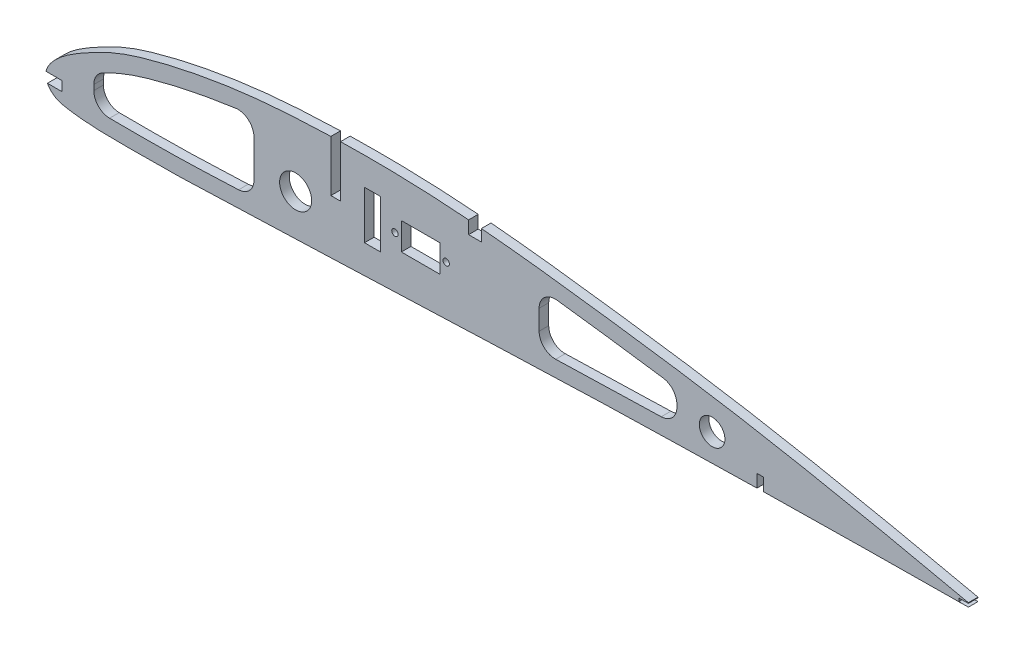
SolidWorks part; units mm, degrees
material "轻木"
ref_plane "前视基准面" through (0, 0, 0) normal (0, 0, 1) x (1, 0, 0)
ref_plane "上视基准面" through (0, 0, 0) normal (0, 1, 0) x (1, 0, 0)
ref_plane "右视基准面" through (0, 0, 0) normal (1, 0, 0) x (0, 0, -1)
other "Configuration Table"
curve "曲线1"
  spline degree 3 poles (300, 0.375, 0) (299.2857, 0.5355, 0) (297.8572, 0.8566, 0) (295.7147, 1.3378, 0) (293.5725, 1.8185, 0) (291.4302, 2.2982, 0) (289.2875, 2.7769, 0) (287.1442, 3.2543, 0) (285.001, 3.7299, 0) (282.8583, 4.2033, 0) (280.7163, 4.6744, 0) (278.5743, 5.1433, 0) (276.432, 5.6099, 0) (274.2889, 6.0741, 0) (272.145, 6.5358, 0) (269.2891, 7.1472, 0) (265.721, 7.9038, 0) (261.4399, 8.8, 0) (257.1573, 9.6847, 0) (252.8725, 10.5577, 0) (248.585, 11.4191, 0) (244.2942, 12.2686, 0) (240.0067, 13.1048, 0) (235.7231, 13.9276, 0) (231.4437, 14.735, 0) (227.1623, 15.5265, 0) (222.8779, 16.3002, 0) (218.5899, 17.0545, 0) (214.2976, 17.7876, 0) (210.0082, 18.4964, 0) (205.7223, 19.1793, 0) (201.441, 19.8388, 0) (197.1575, 20.4787, 0) (192.8717, 21.1016, 0) (188.5834, 21.71, 0) (184.2928, 22.3067, 0) (180.0042, 22.8936, 0) (175.7188, 23.4732, 0) (171.4371, 24.0431, 0) (167.1545, 24.6013, 0) (162.8704, 25.1452, 0) (158.5838, 25.6724, 0) (154.2938, 26.1804, 0) (150.0066, 26.6658, 0) (145.7226, 27.1265, 0) (141.4425, 27.5584, 0) (137.1601, 27.958, 0) (132.875, 28.3213, 0) (128.5869, 28.6439, 0) (124.2953, 28.9218, 0) (120.0053, 29.1506, 0) (115.7177, 29.3264, 0) (111.4337, 29.4514, 0) (107.1488, 29.5275, 0) (102.863, 29.5565, 0) (98.5762, 29.5401, 0) (94.2882, 29.4801, 0) (89.9957, 29.378, 0) (85.6999, 29.236, 0) (81.4026, 29.047, 0) (77.1093, 28.8043, 0) (72.8211, 28.5008, 0) (68.5389, 28.1296, 0) (64.264, 27.6835, 0) (60.7007, 27.2426, 0) (57.8461, 26.8442, 0) (55.696, 26.5216, 0) (53.5496, 26.1773, 0) (51.4067, 25.8115, 0) (49.2673, 25.4247, 0) (47.1314, 25.0171, 0) (44.9882, 24.5868, 0) (42.838, 24.1341, 0) (40.6818, 23.6568, 0) (38.5315, 23.1552, 0) (36.3875, 22.6273, 0) (34.2503, 22.0712, 0) (32.1202, 21.4847, 0) (30.3423, 20.9664, 0) (28.9132, 20.5311, 0) (27.8303, 20.1897, 0) (26.7518, 19.8362, 0) (25.6784, 19.4687, 0) (24.6112, 19.0858, 0) (23.551, 18.6856, 0) (22.4821, 18.2598, 0) (21.4059, 17.8057, 0) (20.3222, 17.3242, 0) (19.2465, 16.8243, 0) (18.1774, 16.3076, 0) (17.1139, 15.7762, 0) (16.0546, 15.2317, 0) (14.9819, 14.6674, 0) (13.8954, 14.0851, 0) (12.7977, 13.4827, 0) (11.7087, 12.8677, 0) (10.6313, 12.2387, 0) (9.5687, 11.5942, 0) (8.5237, 10.9329, 0) (7.6518, 10.3543, 0) (6.9458, 9.8665, 0) (6.3985, 9.4746, 0) (5.8573, 9.0705, 0) (5.3218, 8.651, 0) (4.7913, 8.2128, 0) (4.2653, 7.7527, 0) (3.6165, 7.1497, 0) (2.8604, 6.3846, 0) (2.0362, 5.4343, 0) (1.2959, 4.4252, 0) (0.6772, 3.3675, 0) (0.2189, 2.2697, 0) (-0.0383, 1.1392, 0) (-0.0456, 0.0749, 0) (0.1619, -0.885, 0) (0.4986, -1.7375, 0) (0.9635, -2.5517, 0) (1.5376, -3.3119, 0) (2.2026, -4.0019, 0) (2.94, -4.6051, 0) (3.6355, -5.044, 0) (4.2555, -5.3464, 0) (4.779, -5.5548, 0) (5.3118, -5.728, 0) (5.8521, -5.8723, 0) (6.398, -5.9938, 0) (6.9478, -6.0987, 0) (7.671, -6.2224, 0) (8.5669, -6.3647, 0) (9.636, -6.5177, 0) (10.7063, -6.6545, 0) (11.7778, -6.7754, 0) (12.8506, -6.8809, 0) (13.9246, -6.9713, 0) (14.9978, -7.047, 0) (16.0697, -7.1082, 0) (17.1403, -7.1566, 0) (18.2115, -7.1941, 0) (19.2831, -7.2222, 0) (20.3552, -7.2427, 0) (21.4275, -7.2573, 0) (22.4998, -7.2676, 0) (23.5718, -7.2752, 0) (24.6434, -7.2803, 0) (25.7147, -7.2832, 0) (26.7859, -7.2843, 0) (27.8572, -7.2839, 0) (28.9285, -7.2822, 0) (30.3573, -7.2788, 0) (32.1433, -7.2727, 0) (34.2864, -7.2613, 0) (36.4292, -7.2444, 0) (38.5718, -7.2208, 0) (40.7144, -7.1891, 0) (42.8572, -7.148, 0) (45.0005, -7.0962, 0) (47.1439, -7.0325, 0) (49.2871, -6.9587, 0) (51.4297, -6.8772, 0) (53.572, -6.7902, 0) (55.7143, -6.6999, 0) (57.857, -6.6086, 0) (60.7142, -6.4884, 0) (64.2858, -6.3465, 0) (68.5714, -6.1868, 0) (72.8565, -6.0353, 0) (77.1416, -5.8893, 0) (81.427, -5.7463, 0) (85.7132, -5.6038, 0) (90.0001, -5.4593, 0) (94.287, -5.3101, 0) (98.5731, -5.1566, 0) (102.8583, -4.9992, 0) (107.1431, -4.8383, 0) (111.4281, -4.6742, 0) (115.7138, -4.5074, 0) (120.0001, -4.3383, 0) (124.2865, -4.1673, 0) (128.5722, -3.9953, 0) (132.8572, -3.8233, 0) (137.142, -3.6525, 0) (141.4271, -3.4838, 0) (145.7131, -3.3181, 0) (149.9996, -3.1567, 0) (154.286, -3.0004, 0) (158.5714, -2.8495, 0) (162.8564, -2.7043, 0) (167.1412, -2.5651, 0) (171.4266, -2.4321, 0) (175.7128, -2.3056, 0) (179.9996, -2.1858, 0) (184.2862, -2.0731, 0) (188.5719, -1.9664, 0) (192.857, -1.8646, 0) (197.1419, -1.7668, 0) (201.4272, -1.6719, 0) (205.7132, -1.5788, 0) (209.9999, -1.4865, 0) (214.2864, -1.3941, 0) (218.5722, -1.3027, 0) (222.8572, -1.2136, 0) (227.142, -1.128, 0) (231.4272, -1.0471, 0) (235.7132, -0.9723, 0) (239.9998, -0.9046, 0) (244.2864, -0.8454, 0) (248.5722, -0.7928, 0) (252.8573, -0.7451, 0) (257.1422, -0.7003, 0) (261.4274, -0.6568, 0) (265.7134, -0.6127, 0) (269.2855, -0.574, 0) (272.1433, -0.5408, 0) (274.2862, -0.5157, 0) (276.4287, -0.4908, 0) (278.5712, -0.4671, 0) (280.7137, -0.4452, 0) (282.8567, -0.4258, 0) (285, -0.4096, 0) (287.1432, -0.3973, 0) (289.2862, -0.3884, 0) (291.4287, -0.3824, 0) (293.5711, -0.3786, 0) (295.7137, -0.3765, 0) (297.8567, -0.3754, 0) (299.2855, -0.3751, 0) (300, -0.375, 0) knots 0 0 0 0 0.003574 0.007146 0.010718 0.01429 0.017862 0.021434 0.025008 0.028577 0.032145 0.035713 0.03928 0.042847 0.046415 0.049985 0.057103 0.064219 0.071333 0.078448 0.085563 0.092679 0.099797 0.106885 0.11397 0.121053 0.128137 0.13522 0.142305 0.149391 0.15644 0.163488 0.170534 0.17758 0.184627 0.191675 0.198725 0.205755 0.212782 0.219809 0.226834 0.233861 0.240889 0.24792 0.254921 0.26192 0.268917 0.275914 0.28291 0.289907 0.296905 0.303879 0.310852 0.317824 0.324796 0.331771 0.338748 0.345728 0.352728 0.359727 0.366723 0.373717 0.380709 0.387701 0.394695 0.398233 0.40177 0.405307 0.408843 0.41238 0.415918 0.419457 0.42305 0.426643 0.430235 0.433828 0.43742 0.441014 0.444611 0.446459 0.448306 0.450153 0.451999 0.453844 0.455687 0.45753 0.459459 0.461388 0.463318 0.465249 0.467183 0.469121 0.471062 0.4731 0.475138 0.477173 0.479204 0.481227 0.483239 0.48524 0.486334 0.487428 0.488525 0.48963 0.490748 0.491883 0.493041 0.495071 0.497131 0.499176 0.501171 0.503098 0.50496 0.506796 0.508242 0.509728 0.511253 0.512804 0.514366 0.515919 0.517444 0.518368 0.519283 0.520192 0.521101 0.522011 0.522922 0.523833 0.525592 0.527349 0.529104 0.530859 0.532612 0.534366 0.53612 0.537863 0.539607 0.54135 0.543094 0.544839 0.546584 0.548329 0.550073 0.551817 0.55356 0.555302 0.557045 0.558788 0.560532 0.564019 0.567506 0.570992 0.574478 0.577965 0.581452 0.584939 0.588429 0.591918 0.595406 0.598895 0.602383 0.605872 0.609363 0.616342 0.623319 0.630295 0.637271 0.644247 0.651224 0.658203 0.665183 0.672161 0.679137 0.686114 0.69309 0.700068 0.707048 0.714028 0.721006 0.727983 0.73496 0.741937 0.748915 0.755896 0.762874 0.769851 0.776826 0.783801 0.790777 0.797753 0.804732 0.811709 0.818683 0.825657 0.83263 0.839604 0.846578 0.853555 0.860532 0.867506 0.874479 0.881452 0.888424 0.895399 0.902375 0.90935 0.916324 0.923296 0.930267 0.937239 0.944213 0.951188 0.954676 0.958163 0.961649 0.965135 0.96862 0.972107 0.975595 0.979082 0.982569 0.986054 0.98954 0.993026 0.996512 1 1 1 1
curve "曲线2"
  spline degree 3 poles (299.6892, 0.0825, 0) (300.1498, -0.0478, 0) (299.7114, 0.1074, 0) (299.5104, 0.1872, 0) (299.2477, 0.2871, 0) (298.8504, 0.4413, 0) (298.294, 0.6613, 0) (297.5919, 0.9463, 0) (296.8903, 1.2362, 0) (296.0644, 1.581, 0) (295.1136, 1.9799, 0) (294.0373, 2.431, 0) (292.9597, 2.8788, 0) (291.7683, 3.3665, 0) (290.4608, 3.8877, 0) (289.0365, 4.4399, 0) (287.6073, 4.9796, 0) (286.0635, 5.5484, 0) (284.4048, 6.1444, 0) (282.6311, 6.7664, 0) (280.8534, 7.377, 0) (278.9651, 8.0149, 0) (276.9667, 8.6805, 0) (274.8582, 9.373, 0) (272.7471, 10.0574, 0) (270.5382, 10.7652, 0) (268.2318, 11.4959, 0) (265.8278, 12.2485, 0) (263.4214, 12.9932, 0) (260.9293, 13.7558, 0) (258.3517, 14.5354, 0) (255.6885, 15.3308, 0) (253.0225, 16.1168, 0) (250.2835, 16.9138, 0) (247.4714, 17.7205, 0) (244.5864, 18.536, 0) (241.6982, 19.3402, 0) (238.749, 20.1489, 0) (235.7391, 20.9612, 0) (232.6684, 21.7757, 0) (229.594, 22.5763, 0) (226.4711, 23.374, 0) (223.2997, 24.1675, 0) (220.08, 24.9553, 0) (216.8561, 25.726, 0) (213.5945, 26.4871, 0) (210.2953, 27.2373, 0) (206.9588, 27.975, 0) (203.6178, 28.6919, 0) (200.2497, 29.3918, 0) (196.8549, 30.0732, 0) (193.4336, 30.7349, 0) (190.0077, 31.3718, 0) (186.5618, 31.9862, 0) (183.0963, 32.577, 0) (179.6117, 33.1436, 0) (176.1229, 33.6833, 0) (172.6234, 34.197, 0) (169.1136, 34.6844, 0) (165.5943, 35.1447, 0) (162.0713, 35.5767, 0) (158.5465, 35.9798, 0) (155.0205, 36.3535, 0) (151.4939, 36.6979, 0) (147.9646, 37.0129, 0) (144.4431, 37.2978, 0) (140.9302, 37.5529, 0) (137.4264, 37.7777, 0) (133.9208, 37.9727, 0) (130.4332, 38.1365, 0) (126.9642, 38.269, 0) (123.5147, 38.3706, 0) (120.0643, 38.4412, 0) (116.6408, 38.4803, 0) (113.2449, 38.4881, 0) (109.8772, 38.4649, 0) (106.5099, 38.4098, 0) (103.1795, 38.3231, 0) (99.8867, 38.2053, 0) (96.6323, 38.0567, 0) (93.3796, 37.8749, 0) (90.1728, 37.6618, 0) (87.0127, 37.4182, 0) (83.9, 37.1447, 0) (80.7905, 36.8368, 0) (77.7347, 36.4989, 0) (74.7332, 36.1323, 0) (71.7867, 35.7377, 0) (68.8452, 35.3075, 0) (65.9638, 34.8492, 0) (63.1431, 34.3642, 0) (60.3838, 33.8535, 0) (57.6314, 33.3063, 0) (54.9457, 32.7337, 0) (52.327, 32.1376, 0) (49.7758, 31.5197, 0) (47.2337, 30.8655, 0) (44.763, 30.1905, 0) (42.364, 29.4973, 0) (40.0371, 28.7872, 0) (37.7217, 28.0406, 0) (35.4836, 27.2778, 0) (33.323, 26.5013, 0) (31.2399, 25.7132, 0) (29.1709, 24.8888, 0) (27.1829, 24.0541, 0) (25.2756, 23.212, 0) (23.4491, 22.3647, 0) (21.6401, 21.481, 0) (19.9159, 20.5922, 0) (18.2759, 19.7016, 0) (16.7198, 18.8121, 0) (15.1846, 17.8866, 0) (13.7354, 16.9627, 0) (12.3708, 16.045, 0) (11.0909, 15.1361, 0) (9.8373, 14.192, 0) (8.6721, 13.2572, 0) (7.5935, 12.336, 0) (6.5993, 11.4319, 0) (5.6356, 10.4933, 0) (4.7571, 9.5716, 0) (3.961, 8.6731, 0) (3.2484, 7.802, 0) (2.5791, 6.9017, 0) (2.0018, 6.0303, 0) (1.5119, 5.1928, 0) (1.098, 4.3932, 0) (0.723, 3.565, 0) (0.4148, 2.7772, 0) (0.1635, 2.0409, 0) (-0.0076, 1.362, 0) (-0.0857, 0.6761, 0) (-0.0312, 0.0318, 0) (0.1575, -0.5446, 0) (0.4284, -1.0495, 0) (0.7766, -1.5095, 0) (1.2499, -1.9767, 0) (1.8739, -2.4002, 0) (2.6419, -2.7457, 0) (3.4475, -3.0028, 0) (4.3968, -3.243, 0) (5.4726, -3.4987, 0) (6.6732, -3.7581, 0) (7.8724, -3.9885, 0) (9.2039, -4.2095, 0) (10.6736, -4.4054, 0) (12.2821, -4.571, 0) (13.8972, -4.6995, 0) (15.6445, -4.8094, 0) (17.5211, -4.9053, 0) (19.5261, -4.9826, 0) (21.5305, -5.0368, 0) (23.661, -5.0721, 0) (25.9181, -5.0854, 0) (28.3014, -5.0749, 0) (30.6852, -5.0437, 0) (33.1885, -4.993, 0) (35.8107, -4.9237, 0) (38.5514, -4.8343, 0) (41.2914, -4.7299, 0) (44.1429, -4.6075, 0) (47.1057, -4.467, 0) (50.1792, -4.3077, 0) (53.2522, -4.1367, 0) (56.4269, -3.9498, 0) (59.7026, -3.7473, 0) (63.0791, -3.5293, 0) (66.4551, -3.3033, 0) (69.9209, -3.0645, 0) (73.4761, -2.8134, 0) (77.1202, -2.5502, 0) (80.764, -2.2824, 0) (84.4846, -2.0051, 0) (88.2815, -1.7191, 0) (92.1543, -1.4245, 0) (96.027, -1.128, 0) (99.9621, -0.8252, 0) (103.9592, -0.5167, 0) (108.0179, -0.2032, 0) (112.0767, 0.1098, 0) (116.1823, 0.4251, 0) (120.3344, 0.742, 0) (124.5324, 1.0596, 0) (128.7308, 1.3739, 0) (132.9595, 1.6861, 0) (137.2181, 1.9957, 0) (141.506, 2.3018, 0) (145.7945, 2.6016, 0) (150.096, 2.8954, 0) (154.41, 3.1825, 0) (158.7362, 3.4618, 0) (163.063, 3.7316, 0) (167.3848, 3.9907, 0) (171.7011, 4.2382, 0) (176.0115, 4.4733, 0) (180.3226, 4.6957, 0) (184.6083, 4.9033, 0) (188.8679, 5.0957, 0) (193.1011, 5.2721, 0) (197.335, 5.4325, 0) (201.5222, 5.5742, 0) (205.6623, 5.6969, 0) (209.7546, 5.8004, 0) (213.8473, 5.8854, 0) (217.8716, 5.9498, 0) (221.8268, 5.9942, 0) (225.7124, 6.0188, 0) (229.598, 6.0233, 0) (233.3935, 6.0071, 0) (237.0983, 5.971, 0) (240.7119, 5.9157, 0) (244.325, 5.8393, 0) (247.8275, 5.7436, 0) (251.2186, 5.6301, 0) (254.498, 5.5, 0) (257.7765, 5.3484, 0) (260.9253, 5.1809, 0) (263.9441, 4.9996, 0) (266.8324, 4.8058, 0) (269.7191, 4.5899, 0) (272.4587, 4.362, 0) (275.0509, 4.1249, 0) (277.4951, 3.8799, 0) (279.9368, 3.6105, 0) (282.2113, 3.3338, 0) (284.3185, 3.0537, 0) (286.2585, 2.7745, 0) (288.195, 2.4723, 0) (289.9467, 2.1761, 0) (291.5141, 1.8919, 0) (292.8979, 1.6262, 0) (294.2788, 1.3456, 0) (295.4709, 1.0894, 0) (296.4751, 0.8638, 0) (297.2928, 0.6738, 0) (298.1076, 0.4784, 0) (298.7442, 0.3204, 0) (299.1896, 0.208, 0) (299.4728, 0.1348, 0) (299.6892, 0.0825, 0) (300.1498, -0.0478, 0) (299.7114, 0.1074, 0) knots -0.001345 -0.000897 -0.000449 0 0.000432 0.000863 0.001295 0.001726 0.002951 0.004176 0.0054 0.006625 0.008509 0.010392 0.012274 0.014158 0.016623 0.019088 0.021553 0.024019 0.027053 0.030085 0.033118 0.036152 0.039734 0.043315 0.046896 0.050478 0.054544 0.058608 0.062672 0.066738 0.071224 0.075709 0.080193 0.084679 0.089518 0.094356 0.099193 0.104032 0.10916 0.114286 0.119411 0.124539 0.129889 0.135237 0.140585 0.145936 0.151451 0.156964 0.162478 0.167993 0.173617 0.17924 0.184862 0.190486 0.196184 0.20188 0.207576 0.213274 0.219003 0.22473 0.230457 0.236185 0.241905 0.247622 0.253339 0.259058 0.264725 0.270389 0.276054 0.281721 0.287291 0.29286 0.298428 0.303998 0.309434 0.314867 0.320301 0.325737 0.330995 0.336251 0.341507 0.346766 0.351809 0.356851 0.361892 0.366936 0.371734 0.37653 0.381327 0.386125 0.390654 0.395182 0.399709 0.404238 0.408475 0.41271 0.416945 0.421182 0.425109 0.429034 0.432959 0.436885 0.44048 0.444073 0.447666 0.451261 0.454511 0.457759 0.461007 0.464256 0.467149 0.470041 0.472933 0.475826 0.47836 0.480893 0.483425 0.485956 0.488123 0.490291 0.49246 0.494634 0.496453 0.49827 0.500081 0.501882 0.503328 0.504776 0.506239 0.507727 0.50887 0.510003 0.51111 0.512198 0.513104 0.514027 0.514959 0.515886 0.517235 0.518584 0.51995 0.521324 0.523324 0.525303 0.52727 0.529235 0.531836 0.534446 0.537062 0.539679 0.542921 0.546158 0.549393 0.552628 0.556473 0.560319 0.564166 0.568014 0.57244 0.576864 0.581288 0.585714 0.590681 0.595647 0.600613 0.605581 0.611042 0.616501 0.62196 0.627422 0.633319 0.639214 0.645109 0.651006 0.657275 0.663542 0.669809 0.676078 0.682648 0.689216 0.695784 0.702355 0.70915 0.715943 0.722736 0.729531 0.73647 0.743406 0.750342 0.757281 0.764278 0.771273 0.778268 0.785265 0.792232 0.799197 0.806162 0.81313 0.819969 0.826805 0.833641 0.840479 0.847087 0.853692 0.860297 0.866904 0.873175 0.879445 0.885714 0.891986 0.897819 0.90365 0.909481 0.915314 0.920611 0.925907 0.931202 0.936499 0.941172 0.945842 0.950513 0.955185 0.95915 0.963114 0.967077 0.971042 0.974206 0.977368 0.98053 0.983693 0.985968 0.988241 0.990515 0.992789 0.994144 0.995498 0.996852 0.998206 0.998655 0.999103 0.999551 1 1.000432 1.000863 1.001295 periodic
sketch "草图1" plane through (0, 0, 0) normal (0, 0, 1) x (1, 0, 0)
  line L1 (290, 2.6177) -> (290, -0.3866)
  line L2 (289, 1.8162) -> (289, 0.6101)
  line L3 (0, 0) -> (0, 30) construction
  line L4 (-6, -1.5) -> (6, -1.5)
  line L5 (-6, -1.5) -> (-6, 1.5)
  line L6 (-6, 1.5) -> (6, 1.5)
  line L7 (6, -1.5) -> (6, 1.5)
  line L8 (-6, -1.5) -> (6, 1.5) construction
  line L9 (-6, 1.5) -> (6, -1.5) construction
  line L10 (-1000, 0) -> (49000, 0) construction
  line L11 (90, 29.3715) -> (93, 29.3715)
  line L12 (90, 29.3715) -> (90, 12.3715)
  line L13 (90, 12.3715) -> (93, 12.3715)
  line L14 (93, 29.3715) -> (93, 12.3715)
  line L16 (223, -1.2113) -> (225, -1.2113)
  line L17 (223, -1.2113) -> (223, 3.7887)
  line L18 (223, 3.7887) -> (225, 3.7887)
  line L19 (225, -1.2113) -> (225, 3.7887)
  line L20 (289, 0.6101) -> (286, 0.6101)
  line L21 (289, 0.6101) -> (289, 1.6101)
  line L22 (289, 1.6101) -> (286, 1.6101)
  line L23 (286, 0.6101) -> (286, 1.6101)
  circle A0 centre (79, 8) radius 5
  circle A1 centre (209, 8) radius 4
  spline S0 degree 3 poles (2082.6855, 3477.6386) (932.8124, -150.5674) (615.5616, -70.5075) (295.7147, 1.3378) (293.5725, 1.8185) (291.4302, 2.2982) (289.2875, 2.7769) (287.1442, 3.2543) (285.001, 3.7299) (282.8583, 4.2033) (280.7163, 4.6744) (278.5743, 5.1433) (276.432, 5.6099) (274.2889, 6.0741) (272.145, 6.5358) (269.2891, 7.1472) (265.721, 7.9038) (261.4399, 8.8) (257.1573, 9.6847) (252.8725, 10.5577) (248.585, 11.4191) (244.2942, 12.2686) (240.0067, 13.1048) (234.2978, 14.2013) (228.5907, 15.2685) (222.8779, 16.3002) (218.5899, 17.0545) (214.2976, 17.7876) (210.0082, 18.4964) (205.7223, 19.1793) (201.441, 19.8388) (197.1575, 20.4787) (192.8717, 21.1016) (188.5834, 21.71) (184.2928, 22.3067) (180.0042, 22.8936) (175.7188, 23.4732) (171.4371, 24.0431) (167.1545, 24.6013) (162.8704, 25.1452) (158.5838, 25.6724) (154.2938, 26.1804) (150.0066, 26.6658) (145.7226, 27.1265) (141.4425, 27.5584) (137.1601, 27.958) (132.875, 28.3213) (128.5869, 28.6439) (124.2953, 28.9218) (120.0053, 29.1506) (115.7177, 29.3264) (111.4337, 29.4514) (107.1488, 29.5275) (102.863, 29.5565) (98.5762, 29.5401) (94.2882, 29.4801) (89.9957, 29.378) (85.6999, 29.236) (81.4026, 29.047) (77.1093, 28.8043) (72.8211, 28.5008) (68.5389, 28.1296) (64.264, 27.6835) (60.7007, 27.2426) (57.1284, 26.744) (53.5478, 26.188) (49.9791, 25.5605) (47.1314, 25.0171) (44.9882, 24.5868) (42.838, 24.1341) (40.6818, 23.6568) (38.5315, 23.1552) (36.3875, 22.6273) (34.2503, 22.0712) (32.1202, 21.4847) (30.3423, 20.9664) (28.9132, 20.5311) (27.8303, 20.1897) (26.7518, 19.8362) (25.6784, 19.4687) (24.6112, 19.0858) (23.551, 18.6856) (22.4821, 18.2598) (21.4059, 17.8057) (20.3222, 17.3242) (19.2465, 16.8243) (18.1774, 16.3076) (17.1139, 15.7762) (16.0546, 15.2317) (14.9819, 14.6674) (13.8954, 14.0851) (12.7977, 13.4827) (11.7087, 12.8677) (10.6313, 12.2387) (9.5687, 11.5942) (8.5237, 10.9329) (7.6518, 10.3543) (6.9458, 9.8665) (6.3985, 9.4746) (5.8573, 9.0705) (5.3218, 8.651) (4.7913, 8.2128) (4.2653, 7.7527) (3.6165, 7.1497) (2.8604, 6.3846) (2.0362, 5.4343) (1.2959, 4.4252) (0.6772, 3.3675) (0.2189, 2.2697) (-0.0383, 1.1392) (-0.0456, 0.0749) (0.1619, -0.885) (0.4986, -1.7375) (0.9635, -2.5517) (1.5376, -3.3119) (2.2026, -4.0019) (2.94, -4.6051) (3.6355, -5.044) (4.2555, -5.3464) (4.779, -5.5548) (5.3118, -5.728) (5.8521, -5.8723) (6.398, -5.9938) (6.9478, -6.0987) (7.671, -6.2224) (8.5669, -6.3647) (9.9918, -6.5686) (11.4199, -6.7402) (12.8506, -6.8809) (13.9246, -6.9713) (14.9978, -7.047) (16.0697, -7.1082) (17.1403, -7.1566) (18.2115, -7.1941) (19.2831, -7.2222) (20.3552, -7.2427) (21.4275, -7.2573) (22.4998, -7.2676) (23.5718, -7.2752) (24.6434, -7.2803) (25.7147, -7.2832) (27.143, -7.2847) (28.5715, -7.283) (30.3573, -7.2788) (32.1433, -7.2727) (34.2864, -7.2613) (36.4292, -7.2444) (38.5718, -7.2208) (40.7144, -7.1891) (42.8572, -7.148) (45.0005, -7.0962) (47.1439, -7.0325) (49.2871, -6.9587) (51.4297, -6.8772) (54.2862, -6.7612) (57.1429, -6.6386) (60.7142, -6.4884) (64.2858, -6.3465) (69.9995, -6.1336) (75.7132, -5.9369) (81.427, -5.7463) (85.7132, -5.6038) (90.0001, -5.4593) (94.287, -5.3101) (98.5731, -5.1566) (102.8583, -4.9992) (108.5717, -4.7846) (114.2856, -4.5638) (120.0001, -4.3383) (124.2865, -4.1673) (128.5722, -3.9953) (132.8572, -3.8233) (137.142, -3.6525) (141.4271, -3.4838) (145.7131, -3.3181) (149.9996, -3.1567) (154.286, -3.0004) (158.5714, -2.8495) (164.2846, -2.656) (171.4272, -2.4288) (179.9991, -2.1823) (187.1429, -2.0003) (192.857, -1.8646) (197.1419, -1.7668) (201.4272, -1.6719) (205.7132, -1.5788) (209.9999, -1.4865) (214.2864, -1.3941) (218.5722, -1.3027) (222.8572, -1.2136) (227.142, -1.128) (231.4272, -1.0471) (235.7132, -0.9723) (239.9998, -0.9046) (244.2864, -0.8454) (248.5722, -0.7928) (252.8573, -0.7451) (258.5708, -0.6854) (264.285, -0.6282) (269.2855, -0.574) (272.1433, -0.5408) (274.2862, -0.5157) (276.4287, -0.4908) (278.5712, -0.4671) (280.7137, -0.4452) (282.8567, -0.4258) (285, -0.4096) (287.1432, -0.3973) (289.2862, -0.3884) (291.4287, -0.3824) (293.5711, -0.3786) (295.7137, -0.3765) (545.0303, -0.2592) (793.6356, -11.4767) (1040.5265, 3875.8151) knots -1.589363 -1.589363 -1.589363 -1.589363 0.003574 0.007146 0.010718 0.01429 0.017862 0.021434 0.025008 0.028577 0.032145 0.035713 0.03928 0.042847 0.046415 0.049985 0.057103 0.064219 0.071333 0.078448 0.085563 0.092679 0.099797 0.106885 0.121053 0.128137 0.13522 0.142305 0.149391 0.15644 0.163488 0.170534 0.17758 0.184627 0.191675 0.198725 0.205755 0.212782 0.219809 0.226834 0.233861 0.240889 0.24792 0.254921 0.26192 0.268917 0.275914 0.28291 0.289907 0.296905 0.303879 0.310852 0.317824 0.324796 0.331771 0.338748 0.345728 0.352728 0.359727 0.366723 0.373717 0.380709 0.387701 0.394695 0.398233 0.405307 0.41238 0.415918 0.419457 0.42305 0.426643 0.430235 0.433828 0.43742 0.441014 0.444611 0.446459 0.448306 0.450153 0.451999 0.453844 0.455687 0.45753 0.459459 0.461388 0.463318 0.465249 0.467183 0.469121 0.471062 0.4731 0.475138 0.477173 0.479204 0.481227 0.483239 0.48524 0.486334 0.487428 0.488525 0.48963 0.490748 0.491883 0.493041 0.495071 0.497131 0.499176 0.501171 0.503098 0.50496 0.506796 0.508242 0.509728 0.511253 0.512804 0.514366 0.515919 0.517444 0.518368 0.519283 0.520192 0.521101 0.522011 0.522922 0.523833 0.525592 0.527349 0.530859 0.532612 0.534366 0.53612 0.537863 0.539607 0.54135 0.543094 0.544839 0.546584 0.548329 0.550073 0.551817 0.55356 0.555302 0.558788 0.560532 0.564019 0.567506 0.570992 0.574478 0.577965 0.581452 0.584939 0.588429 0.591918 0.595406 0.598895 0.605872 0.609363 0.616342 0.623319 0.637271 0.644247 0.651224 0.658203 0.665183 0.672161 0.679137 0.686114 0.700068 0.707048 0.714028 0.721006 0.727983 0.73496 0.741937 0.748915 0.755896 0.762874 0.769851 0.776826 0.790777 0.804732 0.818683 0.825657 0.83263 0.839604 0.846578 0.853555 0.860532 0.867506 0.874479 0.881452 0.888424 0.895399 0.902375 0.90935 0.916324 0.923296 0.930267 0.944213 0.951188 0.954676 0.958163 0.961649 0.965135 0.96862 0.972107 0.975595 0.979082 0.982569 0.986054 0.98954 0.993026 0.996512 2.206461 2.206461 2.206461 2.206461 only from (300, 0.375) to (300, -0.375) construction
  spline S1 degree 3 poles (290, 2.6177) (289.0482, 2.8302) (287.3817, 3.2016) (285.001, 3.7299) (282.8583, 4.2033) (280.7163, 4.6744) (278.5743, 5.1433) (276.432, 5.6099) (274.2889, 6.0741) (272.145, 6.5358) (269.2891, 7.1472) (265.721, 7.9038) (261.4399, 8.8) (257.1573, 9.6847) (252.8725, 10.5577) (248.585, 11.4191) (244.2942, 12.2686) (240.0067, 13.1048) (234.2978, 14.2013) (228.5907, 15.2685) (222.8779, 16.3002) (218.5899, 17.0545) (214.2976, 17.7876) (210.0082, 18.4964) (205.7223, 19.1793) (201.441, 19.8388) (197.1575, 20.4787) (192.8717, 21.1016) (188.5834, 21.71) (184.2928, 22.3067) (180.0042, 22.8936) (175.7188, 23.4732) (171.4371, 24.0431) (167.1545, 24.6013) (162.8704, 25.1452) (158.5838, 25.6724) (154.2938, 26.1804) (150.0066, 26.6658) (145.7226, 27.1265) (141.4425, 27.5584) (137.1601, 27.958) (132.875, 28.3213) (128.5869, 28.6439) (124.2953, 28.9218) (120.0053, 29.1506) (115.7177, 29.3264) (111.4337, 29.4514) (107.1488, 29.5275) (102.863, 29.5565) (98.5762, 29.5401) (94.2882, 29.4801) (89.9957, 29.378) (85.6999, 29.236) (81.4026, 29.047) (77.1093, 28.8043) (72.8211, 28.5008) (68.5389, 28.1296) (64.264, 27.6835) (60.7007, 27.2426) (57.1284, 26.744) (53.5478, 26.188) (49.9791, 25.5605) (47.1314, 25.0171) (44.9882, 24.5868) (42.838, 24.1341) (40.6818, 23.6568) (38.5315, 23.1552) (36.3875, 22.6273) (34.2503, 22.0712) (32.1202, 21.4847) (30.3423, 20.9664) (28.9132, 20.5311) (27.8303, 20.1897) (26.7518, 19.8362) (25.6784, 19.4687) (24.6112, 19.0858) (23.551, 18.6856) (22.4821, 18.2598) (21.4059, 17.8057) (20.3222, 17.3242) (19.2465, 16.8243) (18.1774, 16.3076) (17.1139, 15.7762) (16.0546, 15.2317) (14.9819, 14.6674) (13.8954, 14.0851) (12.7977, 13.4827) (11.7087, 12.8677) (10.6313, 12.2387) (9.5687, 11.5942) (8.5237, 10.9329) (7.6518, 10.3543) (6.9458, 9.8665) (6.3985, 9.4746) (5.8573, 9.0705) (5.3218, 8.651) (4.7913, 8.2128) (4.2653, 7.7527) (3.6165, 7.1497) (2.8604, 6.3846) (2.0362, 5.4343) (1.2959, 4.4252) (0.6772, 3.3675) (0.2189, 2.2697) (-0.0383, 1.1392) (-0.0456, 0.0749) (0.1619, -0.885) (0.4986, -1.7375) (0.9635, -2.5517) (1.5376, -3.3119) (2.2026, -4.0019) (2.94, -4.6051) (3.6355, -5.044) (4.2555, -5.3464) (4.779, -5.5548) (5.3118, -5.728) (5.8521, -5.8723) (6.398, -5.9938) (6.9478, -6.0987) (7.671, -6.2224) (8.5669, -6.3647) (9.9918, -6.5686) (11.4199, -6.7402) (12.8506, -6.8809) (13.9246, -6.9713) (14.9978, -7.047) (16.0697, -7.1082) (17.1403, -7.1566) (18.2115, -7.1941) (19.2831, -7.2222) (20.3552, -7.2427) (21.4275, -7.2573) (22.4998, -7.2676) (23.5718, -7.2752) (24.6434, -7.2803) (25.7147, -7.2832) (27.143, -7.2847) (28.5715, -7.283) (30.3573, -7.2788) (32.1433, -7.2727) (34.2864, -7.2613) (36.4292, -7.2444) (38.5718, -7.2208) (40.7144, -7.1891) (42.8572, -7.148) (45.0005, -7.0962) (47.1439, -7.0325) (49.2871, -6.9587) (51.4297, -6.8772) (54.2862, -6.7612) (57.1429, -6.6386) (60.7142, -6.4884) (64.2858, -6.3465) (69.9995, -6.1336) (75.7132, -5.9369) (81.427, -5.7463) (85.7132, -5.6038) (90.0001, -5.4593) (94.287, -5.3101) (98.5731, -5.1566) (102.8583, -4.9992) (108.5717, -4.7846) (114.2856, -4.5638) (120.0001, -4.3383) (124.2865, -4.1673) (128.5722, -3.9953) (132.8572, -3.8233) (137.142, -3.6525) (141.4271, -3.4838) (145.7131, -3.3181) (149.9996, -3.1567) (154.286, -3.0004) (158.5714, -2.8495) (164.2846, -2.656) (171.4272, -2.4288) (179.9991, -2.1823) (187.1429, -2.0003) (192.857, -1.8646) (197.1419, -1.7668) (201.4272, -1.6719) (205.7132, -1.5788) (209.9999, -1.4865) (214.2864, -1.3941) (218.5722, -1.3027) (222.8572, -1.2136) (227.142, -1.128) (231.4272, -1.0471) (235.7132, -0.9723) (239.9998, -0.9046) (244.2864, -0.8454) (248.5722, -0.7928) (252.8573, -0.7451) (258.5708, -0.6854) (264.285, -0.6282) (269.2855, -0.574) (272.1433, -0.5408) (274.2862, -0.5157) (276.4287, -0.4908) (278.5712, -0.4671) (280.7137, -0.4452) (282.8567, -0.4258) (285, -0.4096) (287.1432, -0.3973) (288.8099, -0.3904) (289.7621, -0.3873) (290, -0.3866) knots 0.016674 0.016674 0.016674 0.016674 0.021434 0.025008 0.028577 0.032145 0.035713 0.03928 0.042847 0.046415 0.049985 0.057103 0.064219 0.071333 0.078448 0.085563 0.092679 0.099797 0.106885 0.121053 0.128137 0.13522 0.142305 0.149391 0.15644 0.163488 0.170534 0.17758 0.184627 0.191675 0.198725 0.205755 0.212782 0.219809 0.226834 0.233861 0.240889 0.24792 0.254921 0.26192 0.268917 0.275914 0.28291 0.289907 0.296905 0.303879 0.310852 0.317824 0.324796 0.331771 0.338748 0.345728 0.352728 0.359727 0.366723 0.373717 0.380709 0.387701 0.394695 0.398233 0.405307 0.41238 0.415918 0.419457 0.42305 0.426643 0.430235 0.433828 0.43742 0.441014 0.444611 0.446459 0.448306 0.450153 0.451999 0.453844 0.455687 0.45753 0.459459 0.461388 0.463318 0.465249 0.467183 0.469121 0.471062 0.4731 0.475138 0.477173 0.479204 0.481227 0.483239 0.48524 0.486334 0.487428 0.488525 0.48963 0.490748 0.491883 0.493041 0.495071 0.497131 0.499176 0.501171 0.503098 0.50496 0.506796 0.508242 0.509728 0.511253 0.512804 0.514366 0.515919 0.517444 0.518368 0.519283 0.520192 0.521101 0.522011 0.522922 0.523833 0.525592 0.527349 0.530859 0.532612 0.534366 0.53612 0.537863 0.539607 0.54135 0.543094 0.544839 0.546584 0.548329 0.550073 0.551817 0.55356 0.555302 0.558788 0.560532 0.564019 0.567506 0.570992 0.574478 0.577965 0.581452 0.584939 0.588429 0.591918 0.595406 0.598895 0.605872 0.609363 0.616342 0.623319 0.637271 0.644247 0.651224 0.658203 0.665183 0.672161 0.679137 0.686114 0.700068 0.707048 0.714028 0.721006 0.727983 0.73496 0.741937 0.748915 0.755896 0.762874 0.769851 0.776826 0.790777 0.804732 0.818683 0.825657 0.83263 0.839604 0.846578 0.853555 0.860532 0.867506 0.874479 0.881452 0.888424 0.895399 0.902375 0.90935 0.916324 0.923296 0.930267 0.944213 0.951188 0.954676 0.958163 0.961649 0.965135 0.96862 0.972107 0.975595 0.979082 0.982569 0.98373 0.98373 0.98373 0.98373
  spline S2 degree 1 poles (289, 1.8162) (289, 0.6101) knots 0 0 1 1 construction
  spline S3 degree 3 poles (289, 1.8162) (276.9573, 4.5023) (258.8616, 8.3976) (234.6482, 13.1528) (216.4485, 16.4789) (198.1829, 19.3716) (179.8506, 21.9241) (161.5032, 24.3586) (143.1279, 26.4732) (124.7122, 28.0438) (106.2546, 28.676) (87.7718, 28.43) (72.4033, 27.5865) (60.1859, 26.2263) (51.081, 24.7981) (42.0339, 23.0001) (34.582, 21.1749) (28.6974, 19.4456) (24.362, 17.9834) (20.1748, 16.2079) (16.0789, 14.1399) (12.0403, 11.9468) (8.1401, 9.5604) (5.1537, 7.3164) (3.1001, 5.2006) (1.8138, 3.4707) (0.9689, 1.5796) (0.9059, -0.2656) (1.7459, -2.0716) (3.1431, -3.6011) (4.8543, -4.6194) (6.9276, -5.1056) (9.209, -5.4548) (12.22, -5.8429) (16.0201, -6.1427) (20.6095, -6.2611) (25.2315, -6.2869) (31.3974, -6.2803) (39.1073, -6.2407) (48.3368, -6.0221) (57.5799, -5.613) (66.8407, -5.2429) (76.0966, -4.9217) (88.436, -4.516) (103.8531, -3.9731) (122.3546, -3.2481) (140.8578, -2.4955) (159.3685, -1.8041) (177.8842, -1.2225) (196.4034, -0.7749) (214.9166, -0.3802) (233.434, 0.0126) (251.9612, 0.2567) (270.4719, 0.4292) (282.8248, 0.5874) (289, 0.6101) knots 0.017978 0.017978 0.017978 0.017978 0.078237 0.108366 0.138495 0.168624 0.198753 0.228882 0.259011 0.28914 0.319269 0.349398 0.379527 0.394592 0.409656 0.424721 0.439785 0.447318 0.45485 0.462382 0.469915 0.477447 0.484979 0.492511 0.496277 0.500044 0.50381 0.507576 0.511342 0.515108 0.518874 0.52264 0.526407 0.530173 0.537705 0.545237 0.552769 0.560302 0.575366 0.590431 0.605495 0.62056 0.635624 0.650689 0.680818 0.710947 0.741076 0.771205 0.801334 0.831463 0.861593 0.891722 0.921851 0.95198 0.982109 0.982109 0.982109 0.982109
  point P8 (0, 0)
  dimension "D9" = 10
  dimension "D10" = 8
  dimension "D1" = 290
  dimension "D2" = 1
  dimension "D3" = 12
  dimension "D4" = 3
  dimension "D5" = 30
  dimension "D6" = 3
  dimension "D7" = 17
  dimension "D8" = 90
  dimension "D11" = 130
  dimension "D12" = 11
  dimension "D13" = 8
  dimension "D14" = 5
  dimension "D15" = 2
  dimension "D16" = 130
  dimension "D17" = 1
  dimension "D18" = 3
extrude "凸台-拉伸1" add sketch "草图1" along normal blind 3 contours L2 S3 | S1 L1
sketch "草图3" plane through (0, 0, 0) normal (0, 0, 1) x (1, 0, 0)
  line L5 (100.5, 4.8715) -> (105.5, 4.8715) construction
  line L6 (90, 12.3715) -> (93, 12.3715) construction
  line L7 (93, 28.4491) -> (93, 12.3715) construction
  line L8 (112, 16.6215) -> (124, 16.6215)
  line L9 (112, 16.6215) -> (112, 8.1215)
  line L10 (112, 8.1215) -> (124, 8.1215)
  line L11 (124, 16.6215) -> (124, 8.1215)
  line L12 (112, 16.6215) -> (124, 8.1215) construction
  line L13 (112, 8.1215) -> (124, 16.6215) construction
  line L14 (118, 12.3715) -> (118, 62.4963) construction
  line L20 (132.9954, 27.3029) -> (136.9954, 27.3029)
  line L21 (132.9954, 27.3029) -> (132.9954, 23.3029)
  line L22 (132.9954, 23.3029) -> (136.9954, 23.3029)
  line L23 (136.9954, 27.3029) -> (136.9954, 23.3029)
  line L25 (16, 5.403) -> (16, 3.7496)
  line L26 (66, 16.1752) -> (66, 4.5297)
  line L27 (155, 14.4146) -> (155, 8.2048)
  line L28 (198, 9.9673) -> (198, 9.1407)
  line L29 (100.5, 19.8715) -> (105.5, 19.8715)
  line L30 (100.5, 19.8715) -> (100.5, 4.8715)
  line L31 (100.5, 4.8715) -> (105.5, 4.8715)
  line L32 (105.5, 19.8715) -> (105.5, 4.8715)
  line L33 (105.5, 4.8715) -> (105.5, 19.8715) construction
  circle A11 centre (110, 12.3715) radius 1
  circle A12 centre (126, 12.3715) radius 1
  arc A17 (198, 9.9673) -> (193.7184, 14.9154) centre (193, 9.9673) ccw
  arc A18 (198, 9.1407) -> (193.1165, 4.142) centre (193, 9.1407) cw
  arc A19 (155, 8.2048) -> (160.1704, 3.2078) centre (160, 8.2048) ccw
  arc A20 (155, 14.4146) -> (160.6135, 19.3768) centre (160, 14.4146) cw
  arc A21 (66, 16.1752) -> (60.3235, 21.1292) centre (61, 16.1752) ccw
  arc A22 (66, 4.5297) -> (61.2015, -0.4662) centre (61, 4.5297) cw
  arc A23 (16, 3.7496) -> (20.9267, -1.2499) centre (21, 3.7496) ccw
  arc A24 (16, 5.403) -> (18.6935, 9.8392) centre (21, 5.403) cw
  spline S0 degree 3 poles (289, 1.8162) (276.9573, 4.5023) (258.8616, 8.3976) (234.6482, 13.1528) (216.4485, 16.4789) (198.1829, 19.3716) (179.8506, 21.9241) (161.5032, 24.3586) (143.1279, 26.4732) (124.7122, 28.0438) (107.9942, 28.6164) (97.4163, 28.5467) (93, 28.4491) knots 0.017978 0.017978 0.017978 0.017978 0.078237 0.108366 0.138495 0.168624 0.198753 0.228882 0.259011 0.28914 0.319269 0.34088 0.34088 0.34088 0.34088 construction
  spline S9 degree 3 poles (2716.0161, -8574.3254) (67.8791, -33.9317) (2.8326, 5.2568) (6.0465, 0.6803) (6.0902, 0.6246) (6.1868, 0.5153) (6.2397, 0.4617) (6.3456, 0.3655) (6.3976, 0.3236) (6.5437, 0.2182) (6.6312, 0.1692) (6.7722, 0.1112) (6.804, 0.099) (6.8878, 0.0698) (6.9381, 0.0536) (7.1139, 0.0015) (7.2645, -0.0375) (7.537, -0.0984) (7.6355, -0.1192) (7.8472, -0.1616) (7.9613, -0.1834) (8.3094, -0.2477) (8.5533, -0.2893) (9.0582, -0.3705) (9.3192, -0.41) (9.8531, -0.4875) (10.1264, -0.5257) (10.9344, -0.635) (11.4671, -0.7017) (12.5267, -0.821) (13.0591, -0.8742) (14.6647, -1.0159) (15.7434, -1.0862) (17.929, -1.1862) (19.0402, -1.2168) (21.2997, -1.2581) (22.4443, -1.2693) (24.7448, -1.282) (25.9034, -1.2838) (29.3811, -1.2835) (31.7096, -1.2772) (36.344, -1.2483) (38.6522, -1.2235) (43.2612, -1.1389) (45.5633, -1.0801) (50.1682, -0.9268) (52.4816, -0.8311) (57.1372, -0.634) (59.4794, -0.5349) (64.1588, -0.348) (66.5002, -0.2589) (73.5178, -0.0049) (78.1885, 0.1484) (87.5159, 0.4597) (92.1745, 0.6196) (101.4932, 0.9531) (106.1515, 1.1269) (120.1319, 1.6658) (129.4563, 2.0501) (148.1311, 2.7844) (157.4781, 3.1298) (171.5046, 3.5762) (176.182, 3.7134) (185.5345, 3.9625) (190.2088, 4.0755) (199.5523, 4.2901) (204.2219, 4.392) (649.5534, 13.9399) (1072.7613, 25.4729) (8192.7802, -4117.9261) knots -0.340541 -0.340541 -0.340541 -0.340541 0.003906 0.003906 0.007813 0.007813 0.011719 0.011719 0.015625 0.015625 0.023438 0.023438 0.025391 0.025391 0.027344 0.027344 0.03125 0.03125 0.033203 0.033203 0.035156 0.035156 0.039063 0.039063 0.042969 0.042969 0.046875 0.046875 0.054688 0.054688 0.0625 0.0625 0.078125 0.078125 0.09375 0.09375 0.109375 0.109375 0.125 0.125 0.15625 0.15625 0.1875 0.1875 0.21875 0.21875 0.25 0.25 0.28125 0.28125 0.3125 0.3125 0.375 0.375 0.4375 0.4375 0.5 0.5 0.625 0.625 0.75 0.75 0.8125 0.8125 0.875 0.875 0.9375 0.9375 6.837005 6.837005 6.837005 6.837005 only from (5.9323, 0.8564) to (222.8977, 4.7881)
  spline S10 degree 3 poles (160.1704, 3.2078) (162.3897, 3.2834) (164.6093, 3.3568) (171.5046, 3.5762) (176.182, 3.7134) (184.9459, 3.9468) (189.0321, 4.0469) (193.1165, 4.142) knots 0.720326 0.720326 0.720326 0.720326 0.75 0.75 0.8125 0.8125 0.867134 0.867134 0.867134 0.867134
  spline S12 degree 3 poles (2473.6517, 4175.1569) (1319.8259, -493.6171) (810.8225, -112.9481) (255.6753, 3.881) (247.6023, 5.5193) (235.4757, 7.8705) (231.4302, 8.6379) (223.342, 10.1274) (219.2984, 10.8484) (211.208, 12.2244) (207.156, 12.8806) (199.0386, 14.1387) (194.9733, 14.7397) (186.8242, 15.9029) (182.7409, 16.4659) (174.5659, 17.5758) (170.4813, 18.121) (158.2342, 19.697) (150.0783, 20.6696) (137.8564, 21.8798) (133.7874, 22.2409) (125.6593, 22.8404) (121.6016, 23.0755) (-377.3735, 43.3939) (-936.3294, -947.1829) (998.7814, 4789.8315) knots -8.354564 -8.354564 -8.354564 -8.354564 0.125 0.125 0.25 0.25 0.3125 0.3125 0.375 0.375 0.4375 0.4375 0.5 0.5 0.5625 0.5625 0.625 0.625 0.75 0.75 0.8125 0.8125 0.875 0.875 8.485481 8.485481 8.485481 8.485481 only from (287.9115, -3.0638) to (93.1104, 23.4504)
  spline S13 degree 3 poles (193.7184, 14.9154) (192.779, 15.0518) (191.8391, 15.1871) (186.8242, 15.9029) (182.7409, 16.4659) (174.5659, 17.5758) (170.4813, 18.121) (164.47, 18.8945) (162.5415, 19.1384) (160.6135, 19.3768) knots 0.485575 0.485575 0.485575 0.485575 0.5 0.5 0.5625 0.5625 0.625 0.625 0.654532 0.654532 0.654532 0.654532
  spline S14 degree 3 poles (5.9575, 0.4062) (5.9575, 0.4062) (5.9576, 0.4062) (5.9578, 0.4064) knots 0.089317 0.089317 0.089317 0.089317 0.089317 0.089317 0.089317 0.089317
  spline S15 degree 3 poles (-881.4296, 8916.1516) (688.5102, -449.1392) (353.2002, 50.7832) (64.1587, 21.6485) (60.4651, 21.183) (53.1092, 20.0468) (49.4459, 19.3843) (42.1587, 17.8687) (38.5334, 17.0196) (33.149, 15.5462) (31.3629, 15.0224) (27.821, 13.8802) (26.0672, 13.2533) (22.6358, 11.8127) (20.9579, 11.0048) (17.648, 9.3036) (16.0082, 8.4228) (13.5937, 7.0224) (12.7968, 6.5418) (11.2302, 5.5376) (10.459, 5.016) (8.9706, 3.8992) (8.2535, 3.3022) (7.272, 2.3101) (6.9596, 1.9643) (6.5302, 1.4143) (6.3938, 1.2256) (6.2082, 0.9302) (6.1495, 0.8297) (6.069, 0.675) (6.0433, 0.6225) (6.0083, 0.5426) (5.9972, 0.5158) (5.9815, 0.4751) (5.9764, 0.4615) (5.9691, 0.441) (5.9667, 0.4341) (5.9633, 0.4238) (5.9621, 0.4203) (5.9605, 0.4151) (5.9599, 0.4133) (5.9092, 0.2508) (-9.3774, -26.124) (4224.357, 7203.798) knots -0.838024 -0.838024 -0.838024 -0.838024 0.022329 0.022329 0.033494 0.033494 0.044659 0.044659 0.055823 0.055823 0.061406 0.061406 0.066988 0.066988 0.07257 0.07257 0.078153 0.078153 0.080944 0.080944 0.083735 0.083735 0.086526 0.086526 0.087922 0.087922 0.08862 0.08862 0.088968 0.088968 0.089143 0.089143 0.08923 0.08923 0.089274 0.089274 0.089296 0.089296 0.089306 0.089306 0.089312 0.089312 0.089817 0.089817 0.089817 0.089817 only from (90.1451, 23.3745) to (5.9578, 0.4064)
  spline S16 degree 3 poles (60.3235, 21.1292) (59.1433, 20.9681) (57.9644, 20.7967) (53.1092, 20.0468) (49.4459, 19.3843) (42.1587, 17.8687) (38.5334, 17.0196) (33.149, 15.5462) (31.3629, 15.0224) (27.821, 13.8802) (26.0672, 13.2533) (22.6358, 11.8127) (20.9579, 11.0048) (19.0996, 10.0497) (18.8964, 9.9447) (18.6935, 9.8392) knots 0.02992 0.02992 0.02992 0.02992 0.033494 0.033494 0.044659 0.044659 0.055823 0.055823 0.061406 0.061406 0.066988 0.066988 0.07257 0.07257 0.073256 0.073256 0.073256 0.073256
  spline S17 degree 3 poles (20.9267, -1.2499) (21.8097, -1.2628) (22.7004, -1.2707) (24.7448, -1.282) (25.9034, -1.2838) (29.3811, -1.2835) (31.7096, -1.2772) (36.344, -1.2483) (38.6522, -1.2235) (43.2612, -1.1389) (45.5633, -1.0801) (50.1682, -0.9268) (52.4816, -0.8311) (56.9324, -0.6427) (59.0674, -0.5523) (61.2015, -0.4662) knots 0.097229 0.097229 0.097229 0.097229 0.109375 0.109375 0.125 0.125 0.15625 0.15625 0.1875 0.1875 0.21875 0.21875 0.25 0.25 0.278501 0.278501 0.278501 0.278501
  point P12 (118, 12.3715)
  dimension "D9" = 8.5
  dimension "D10" = 62
  dimension "D11" = 2
  dimension "D17" = 5
  dimension "D4" = 5
  dimension "D5" = 16
  dimension "D6" = 50
  dimension "D7" = 25
  dimension "D8" = 12
  dimension "D12" = 16
  dimension "D13" = 39.9954
  dimension "D14" = 4
  dimension "D15" = 4
  dimension "D16" = 43
  dimension "D2" = 5
  dimension "D3" = 5
extrude "切除-拉伸2" cut sketch "草图3" along normal through all contours L32 L29 L30 L31 | L9 L8 L11 L10 | A11 | A12 | L21 L20 L23 L22 | S13 A20 L27 A19 S10 A18 L28 A17 | S17 A22 L26 A21 S16 A24 L25 A23
